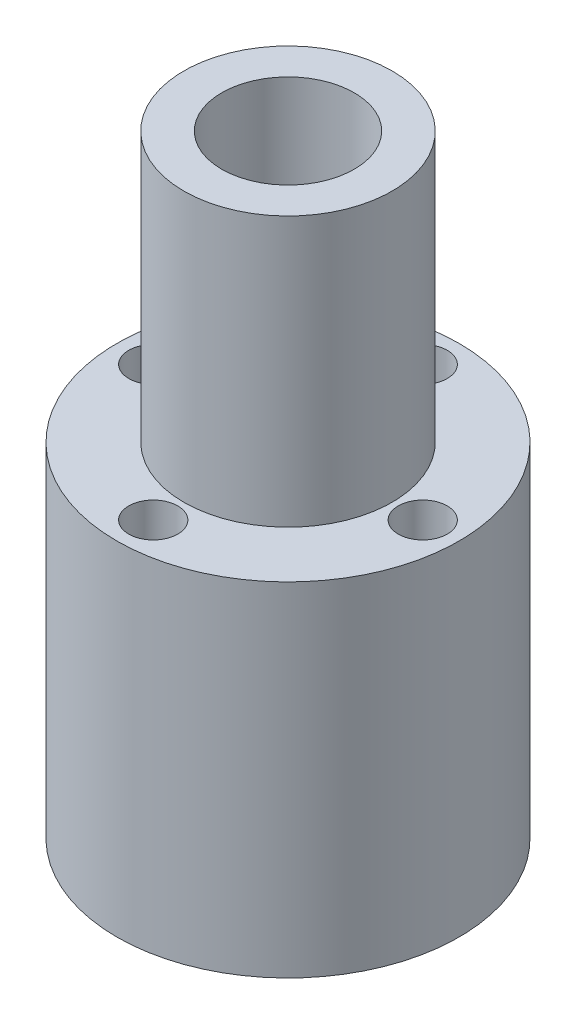
SolidWorks part; units mm, degrees
material "Brass"
ref_plane "Front Plane" through (0, 0, 0) normal (0, 0, 1) x (1, 0, 0)
ref_plane "Top Plane" through (0, 0, 0) normal (0, 1, 0) x (1, 0, 0)
ref_plane "Right Plane" through (0, 0, 0) normal (1, 0, 0) x (0, 0, -1)
sketch "Sketch1" plane through (0, 0, 0) normal (0, 1, 0) x (1, 0, 0)
  circle A0 centre (0, 0) radius 2.7051
  circle A1 centre (0, 0) radius 4.25
  dimension "D1" = 8.5
  dimension "D2" = 5.4102
extrude "Boss-Extrude1" add sketch "Sketch1" along normal blind 11
sketch "Sketch2" plane through (0, 0, 0) normal (0, 1, 0) x (1, 0, 0)
  circle A0 centre (0, 0) radius 1.75
  circle A1 centre (0, 0) radius 6.985
  circle A2 centre (0, 0) radius 5.5 construction
  circle A3 centre (0, 5.5) radius 1
  circle A4 centre (5.5, 0) radius 1
  circle A5 centre (0, -5.5) radius 1
  circle A6 centre (-5.5, 0) radius 1
  circle A7 centre (0, 0) radius 5 construction
  dimension "D1" = 3.5
  dimension "D2" = 13.97
  dimension "D3" = 2
  dimension "D4" = 10
  dimension "D5" = 11
extrude "Boss-Extrude2" add sketch "Sketch2" against normal blind 14
sketch "Sketch3" plane through (0, 0, 0) normal (0, 1, 0) x (1, 0, 0)
  circle A0 centre (0, 0) radius 2.1
  dimension "D1" = 4.2
extrude "Cut-Extrude1" cut sketch "Sketch3" along normal blind 6 from surface at -14 starting at face at (-5.5, -14, 1)
